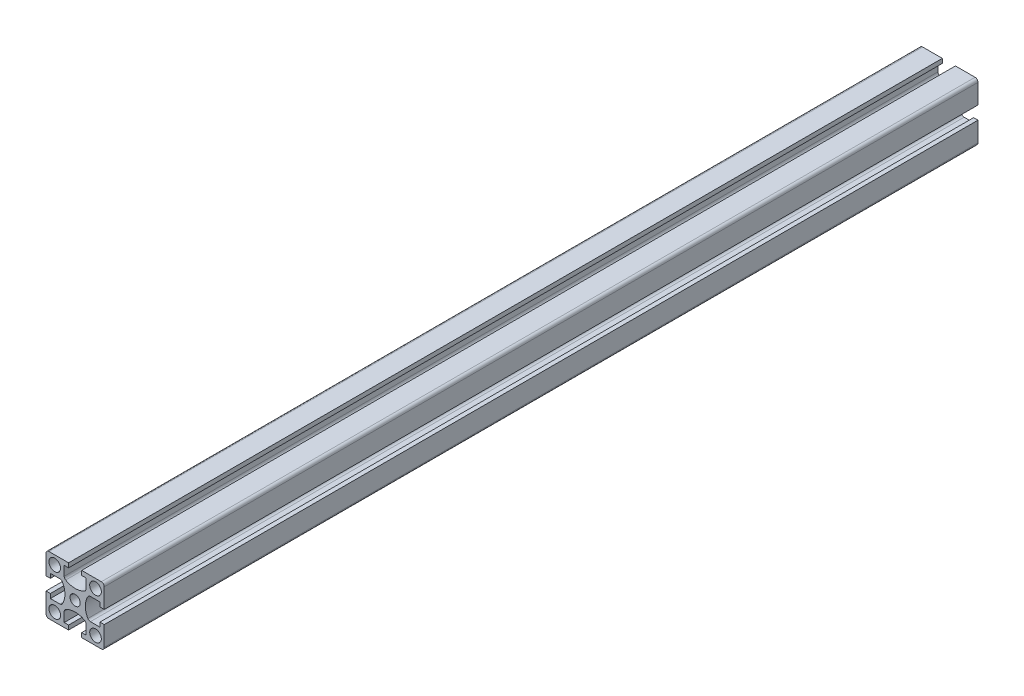
SolidWorks part; units mm, degrees
ref_plane "Front Plane" through (0, 0, 0) normal (0, 0, 1) x (1, 0, 0)
ref_plane "Top Plane" through (0, 0, 0) normal (0, 1, 0) x (1, 0, 0)
ref_plane "Right Plane" through (0, 0, 0) normal (1, 0, 0) x (0, 0, -1)
sketch "Sketch1" plane through (0, 0, 0) normal (0, 0, 1) x (1, 0, 0)
  line L64 (-12.5, 11.25) -> (-12.5, 2.8125)
  line L65 (-12.5, 2.8125) -> (-10.625, 2.8125)
  line L66 (-10.625, 2.8125) -> (-10.625, 4.6875)
  line L67 (-10.625, 4.6875) -> (-6.5461, 4.6875)
  line L68 (-6.5461, -4.6875) -> (-10.625, -4.6875)
  line L69 (-10.625, -4.6875) -> (-10.625, -2.8125)
  line L70 (-10.625, -2.8125) -> (-12.5, -2.8125)
  line L71 (-12.5, -2.8125) -> (-12.5, -11.25)
  line L72 (-11.25, -12.5) -> (-2.8125, -12.5)
  line L73 (-2.8125, -12.5) -> (-2.8125, -10.625)
  line L74 (-2.8125, -10.625) -> (-4.6875, -10.625)
  line L75 (-4.6875, -10.625) -> (-4.6875, -6.5461)
  line L76 (4.6875, -6.5461) -> (4.6875, -10.625)
  line L77 (4.6875, -10.625) -> (2.8125, -10.625)
  line L78 (2.8125, -10.625) -> (2.8125, -12.5)
  line L79 (2.8125, -12.5) -> (11.25, -12.5)
  line L80 (12.5, -11.25) -> (12.5, -2.8125)
  line L81 (12.5, -2.8125) -> (10.625, -2.8125)
  line L82 (10.625, -2.8125) -> (10.625, -4.6875)
  line L83 (10.625, -4.6875) -> (6.5461, -4.6875)
  line L84 (6.5461, 4.6875) -> (10.625, 4.6875)
  line L85 (10.625, 4.6875) -> (10.625, 2.8125)
  line L86 (10.625, 2.8125) -> (12.5, 2.8125)
  line L87 (12.5, 2.8125) -> (12.5, 11.25)
  line L88 (11.25, 12.5) -> (2.8125, 12.5)
  line L89 (2.8125, 12.5) -> (2.8125, 10.625)
  line L90 (2.8125, 10.625) -> (4.6875, 10.625)
  line L91 (4.6875, 10.625) -> (4.6875, 6.5461)
  line L92 (-4.6875, 6.5461) -> (-4.6875, 10.625)
  line L93 (-4.6875, 10.625) -> (-2.8125, 10.625)
  line L94 (-2.8125, 10.625) -> (-2.8125, 12.5)
  line L95 (-2.8125, 12.5) -> (-11.25, 12.5)
  circle A5 centre (-8.75, -8.75) radius 2.5
  circle A6 centre (8.75, -8.75) radius 2.5
  circle A7 centre (8.75, 8.75) radius 2.5
  circle A8 centre (0, 0) radius 2.1875
  circle A9 centre (-8.75, 8.75) radius 2.5
  arc A32 (-11.25, 12.5) -> (-12.5, 11.25) centre (-11.25, 11.25) ccw
  arc A33 (-5.4635, 4.0625) -> (-6.5461, 4.6875) centre (-6.5461, 3.4375) ccw
  arc A34 (-5.4635, -4.0625) -> (-5.4635, 4.0625) centre (-12.5, 0) ccw
  arc A35 (-6.5461, -4.6875) -> (-5.4635, -4.0625) centre (-6.5461, -3.4375) ccw
  arc A36 (-12.5, -11.25) -> (-11.25, -12.5) centre (-11.25, -11.25) ccw
  arc A37 (-4.0625, -5.4635) -> (-4.6875, -6.5461) centre (-3.4375, -6.5461) ccw
  arc A38 (4.0625, -5.4635) -> (-4.0625, -5.4635) centre (0, -12.5) ccw
  arc A39 (4.6875, -6.5461) -> (4.0625, -5.4635) centre (3.4375, -6.5461) ccw
  arc A40 (11.25, -12.5) -> (12.5, -11.25) centre (11.25, -11.25) ccw
  arc A41 (5.4635, -4.0625) -> (6.5461, -4.6875) centre (6.5461, -3.4375) ccw
  arc A42 (5.4635, 4.0625) -> (5.4635, -4.0625) centre (12.5, 0) ccw
  arc A43 (6.5461, 4.6875) -> (5.4635, 4.0625) centre (6.5461, 3.4375) ccw
  arc A44 (12.5, 11.25) -> (11.25, 12.5) centre (11.25, 11.25) ccw
  arc A45 (4.0625, 5.4635) -> (4.6875, 6.5461) centre (3.4375, 6.5461) ccw
  arc A46 (-4.0625, 5.4635) -> (4.0625, 5.4635) centre (0, 12.5) ccw
  arc A47 (-4.6875, 6.5461) -> (-4.0625, 5.4635) centre (-3.4375, 6.5461) ccw
extrude "Boss-Extrude1" add sketch "Sketch1" along normal blind 375
